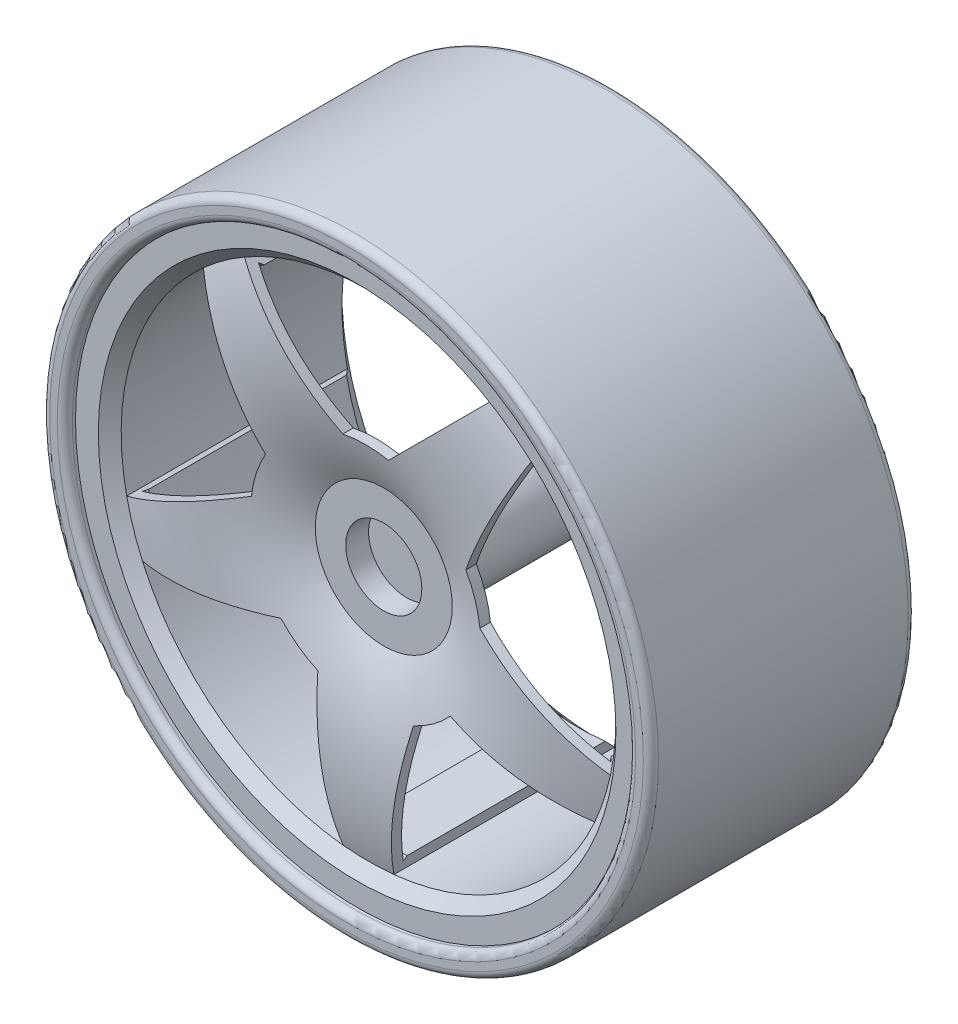
SolidWorks part; units mm, degrees
ref_plane "Front Plane" through (0, 0, 0) normal (0, 0, 1) x (1, 0, 0)
ref_plane "Top Plane" through (0, 0, 0) normal (0, 1, 0) x (1, 0, 0)
ref_plane "Right Plane" through (0, 0, 0) normal (1, 0, 0) x (0, 0, -1)
sketch "Sketch1" plane through (0, 0, 0) normal (1, 0, 0) x (0, 0, -1)
  line L0 (0, 0) -> (0, 15.5) construction
  line L1 (6.5, 15.5) -> (-6.5, 15.5)
  line L2 (-6.5, 15.5) -> (-8, 17)
  line L3 (-8, 17) -> (-8, 18.5)
  line L4 (-8, 18.5) -> (-6.5, 18.5)
  line L5 (-6.5, 18.5) -> (-5, 16.5)
  line L6 (-5, 16.5) -> (5, 16.5)
  line L7 (-10.5579, 0) -> (8.3961, 0) construction
  line L8 (6.5, 15.5) -> (8, 17)
  line L9 (8, 17) -> (8, 18.5)
  line L10 (8, 18.5) -> (6.5, 18.5)
  line L11 (6.5, 18.5) -> (5, 16.5)
  point P16 (0, 16.5)
  dimension "D1" = 6.5
  dimension "D2" = 5
  dimension "D3" = 1.5
  dimension "D4" = 1.5
  dimension "D5" = 15.5
  dimension "D6" = 1
  dimension "D7" = 18.5
  dimension "D8" = 16
revolve "Revolve1" add sketch "Sketch1" angle 360 about L7
sketch "Sketch3" plane through (0, 0, 0) normal (1, 0, 0) x (0, 0, -1)
  line L0 (-6.25, 4.5) -> (-6.25, 2.5)
  line L1 (-6.25, 2.5) -> (-4.75, 2.5)
  line L2 (-4.75, 2.5) -> (-4.75, 0)
  line L3 (-10.5579, 0) -> (8.3961, 0) construction
  line L4 (-4.75, 0) -> (-4, 0)
  line L5 (-4, 0) -> (-4, 2.5)
  line L6 (-4, 2.5) -> (5.75, 2.5)
  line L7 (5.75, 2.5) -> (5.75, 3.25)
  line L8 (5.75, 3.25) -> (-5.5, 3.25)
  line L9 (-5.5, 3.25) -> (-5.5, 4.5)
  line L10 (-6.5, 15.5) -> (-8, 17) construction
  line L11 (-8, 17) -> (-8, 18.5) construction
  line L12 (-7.25, 16.25) -> (-6.7197, 15.7197)
  arc A0 (-6.25, 4.5) -> (-7.25, 16.25) centre (7.4335, 11.5821) cw
  arc A1 (-6.7197, 15.7197) -> (-5.5, 4.5) centre (7.4335, 11.5821) ccw
  point P25 (-7.25, 16.25)
  dimension "D1" = 0.75
  dimension "D2" = 2
  dimension "D3" = 1.5
  dimension "D4" = 11.25
  dimension "D5" = 0.75
  dimension "D6" = 0.75
  dimension "D7" = 2.5
  dimension "D8" = 1.75
  dimension "D9" = 0.75
revolve "Revolve2" add sketch "Sketch3" angle 360 about L4
sketch "Sketch4" plane through (0, 0, 0) normal (0, 0, 1) x (1, 0, 0)
  line L0 (0, 0) -> (0, 16.25) construction
  line L1 (-1.5, 7.4069) -> (-8.151, 14.0579)
  line L2 (1.5, 7.4069) -> (8.151, 14.0579)
  line L3 (6.5808, 3.7154) -> (10.851, 12.0962)
  line L4 (7.5079, 0.8623) -> (15.8886, -3.4079)
  line L5 (5.5672, -5.1106) -> (14.8573, -6.582)
  line L6 (3.1401, -6.874) -> (1.6687, -16.1641)
  line L7 (-3.1401, -6.874) -> (-1.6687, -16.1641)
  line L8 (-5.5672, -5.1106) -> (-14.8573, -6.582)
  line L9 (-7.5079, 0.8623) -> (-15.8886, -3.4079)
  line L10 (-6.5808, 3.7154) -> (-10.851, 12.0962)
  circle A0 centre (0, 0) radius 16.25 construction
  arc A1 (-6.5808, 3.7154) -> (-7.5079, 0.8623) centre (0, 0) ccw
  arc A2 (-10.851, 12.0962) -> (-15.8886, -3.4079) centre (0, 0) ccw
  arc A3 (-5.5672, -5.1106) -> (-3.1401, -6.874) centre (0, 0) ccw
  arc A4 (-14.8573, -6.582) -> (-1.6687, -16.1641) centre (0, 0) ccw
  arc A5 (3.1401, -6.874) -> (5.5672, -5.1106) centre (0, 0) ccw
  arc A6 (1.6687, -16.1641) -> (14.8573, -6.582) centre (0, 0) ccw
  arc A7 (7.5079, 0.8623) -> (6.5808, 3.7154) centre (0, 0) ccw
  arc A8 (15.8886, -3.4079) -> (10.851, 12.0962) centre (0, 0) ccw
  arc A9 (1.5, 7.4069) -> (-1.5, 7.4069) centre (0, 0) ccw
  arc A10 (8.151, 14.0579) -> (-8.151, 14.0579) centre (0, 0) ccw
  point P11 (0, 0)
  point P30 (0, 0)
  dimension "D1" = 3
  dimension "D2" = 45
  dimension "D3" = 5
extrude "Cut-Extrude2" cut sketch "Sketch4" against normal blind 10 and the other way blind 10
sketch "Sketch5" plane through (0, 0, 0) normal (1, 0, 0) x (0, 0, -1)
  line L0 (-8.2, 18.5) -> (-6.5, 18.5)
  line L1 (-6.5, 18.5) -> (-5, 16.5)
  line L2 (-5, 16.5) -> (5, 16.5)
  line L3 (5, 16.5) -> (6.5, 18.5)
  line L4 (6.5, 18.5) -> (8.2, 18.5)
  line L5 (8.7, 19) -> (8.7, 19.5)
  line L6 (8.2, 20) -> (-8.2, 20)
  line L7 (-8.7, 19.5) -> (-8.7, 19)
  line L8 (-6.5, 18.5) -> (-6.5, -18.5) construction
  line L9 (6.5, 18.5) -> (6.5, -18.5) construction
  line L10 (-17.2801, 0) -> (16.5529, 0) construction
  arc A0 (8.7, 19.5) -> (8.2, 20) centre (8.2, 19.5) ccw
  arc A1 (8.2, 18.5) -> (8.7, 19) centre (8.2, 19) ccw
  arc A2 (-8.2, 18.5) -> (-8.7, 19) centre (-8.2, 19) cw
  arc A3 (-8.2, 20) -> (-8.7, 19.5) centre (-8.2, 19.5) ccw
  dimension "D4" = 0.5
  dimension "D1" = 20
  dimension "D2" = 2.2
  dimension "D3" = 2.2
revolve "Revolve3" add sketch "Sketch5" angle 360 about L10
sketch "Sketch6" plane through (0, 0, -5.75) normal (0, 0, -1) x (-1, 0, 0)
  circle A0 centre (0, 0) radius 2.5 construction
  circle A1 centre (0, 0) radius 2.5
  circle A2 centre (0, 0) radius 1.5
  dimension "D1" = 3
extrude "Boss-Extrude1" add sketch "Sketch6" against normal blind 10 from offset 0.2
